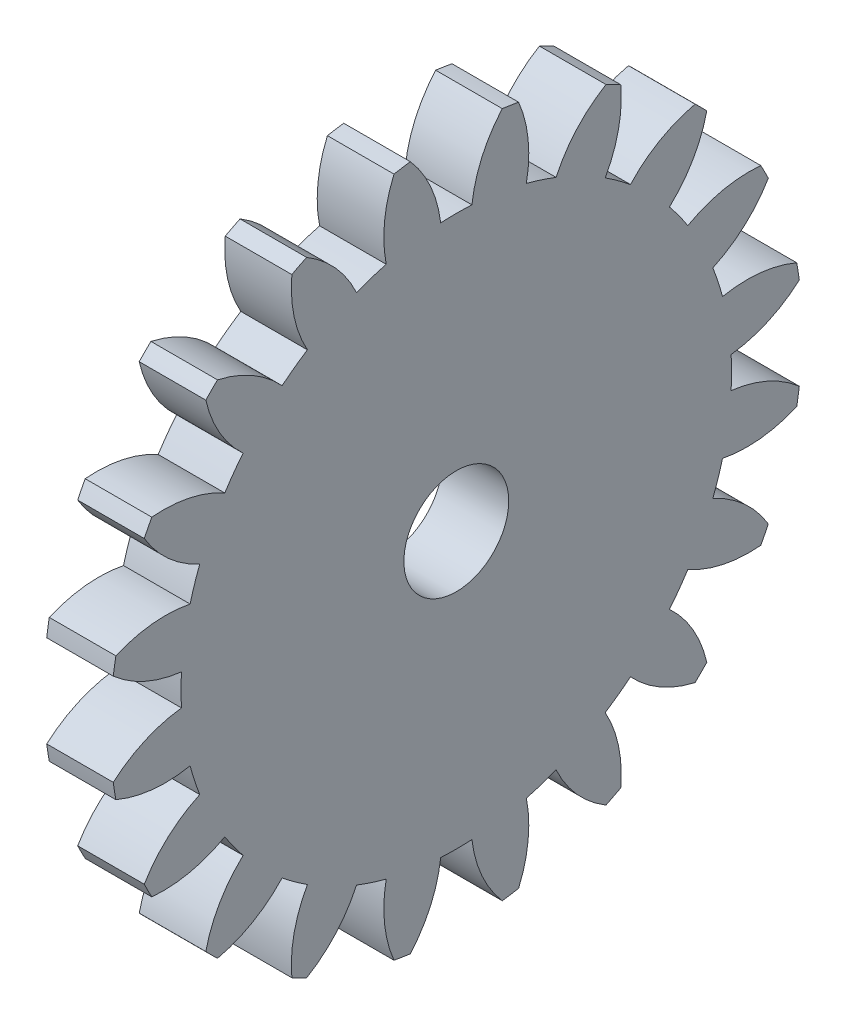
SolidWorks part; units mm, degrees
material "6061 Alloy"
ref_plane "Plane1" through (0, 0, 0) normal (0, 0, 1) x (1, 0, 0)
ref_plane "Plane2" through (0, 0, 0) normal (0, 1, 0) x (1, 0, 0)
ref_plane "Plane3" through (0, 0, 0) normal (1, 0, 0) x (0, 0, -1)
sketch "HoldingSke" plane through (0, 0, 0) normal (0, 1, 0) x (1, 0, 0)
  line L0 (0, 0) -> (0.3132, -0.114)
  line L1 (-15, 0) -> (100, 0) construction
  line L2 (0, 0) -> (-2.1039, 2.3779)
  line L3 (0, 0) -> (-11.863, 4.5341)
  line L4 (0, 0) -> (8.1152, 2.9537)
  line L5 (0, 0) -> (-46.8476, -17.4728)
  line L6 (0, 0) -> (-10.5278, -7.1032)
  line L7 (-2.1039, 2.3779) -> (8.6586, 51.2059)
  line L8 (-76.2, 54.61) -> (-74.4, 54.61)
  line L9 (-71.009, 38.7566) -> (-53.1078, 45.2721)
  line L10 (-76.2, 71.12) -> (104.1128, 71.12)
  line L11 (0, 0) -> (-12.7, 0)
  line L12 (-76.2, 101.6) -> (-76.093, 101.6)
  line L13 (24.9733, 27.94) -> (52.9518, 28.4284)
  line L14 (24.9733, 27.94) -> (24.9743, 27.94)
  line L15 (24.9733, 27.94) -> (100.4006, 29.5858)
  line L16 (-63.627, -3) -> (-12.827, -3)
  circle A0 centre (0, 0) radius 5
  circle A1 centre (0, 0) radius 26.249
  circle A2 centre (0, 0) radius 37.5
  circle A3 centre (0, 0) radius 5
  dimension "MHD" = 52.498
  dimension "Hub_dia" = 75
  dimension "Bore" = 10
  dimension "MBD" = 10
  dimension "Num_teeth" = 20
  dimension "Pitch" = 0.3333
  dimension "Overall_len" = 50
  dimension "Show_teeth" = 20
  dimension "Thickness" = 12.7
  dimension "OAL" = 50.0001
  dimension "T_dim" = 1.8
  dimension "Ap" = 20
  dimension "H" = 19.05
  dimension "Pitch_radius" = 180.3128
  dimension "Width" = 12.7
  dimension "Backlash" = 0.107
  dimension "Addendum_fac" = 1
  dimension "Dedendum_fac" = 1.25
  dimension "Clearance_fac" = 0.25
  dimension "Dedendum_add" = 0.001
  dimension "Module" = 3
sketch "BasProSke" plane through (0, 0, 0) normal (0, 1, 0) x (1, 0, 0)
  line L0 (-10, 0) -> (60, 0) construction
  line L1 (0, 0) -> (0, 33)
  line L2 (0, 0) -> (12.7, 0)
  line L3 (12.7, 0) -> (12.7, 33)
  line L4 (12.7, 33) -> (0, 33)
  dimension "Thickness" = 12.7
  dimension "Diameter" = 66
revolve "Base-Revolve" add sketch "BasProSke" angle 360 about L0
sketch "TooCutSke" plane through (0, 0, 0) normal (1, 0, 0) x (0, 0, -1)
  line L1 (0, 0) -> (0, 107) construction
  line L2 (0, 0) -> (-2.5409, 29.8922) construction
  line L3 (0, 0) -> (-9.3616, 59.1066) construction
  line L4 (-2.5409, 29.8922) -> (-4.6808, 29.5533) construction
  arc A0 (1.4893, 26.2067) -> (-1.4893, 26.2067) centre (0, 0) ccw
  arc A1 (4.4016, 32.7308) -> (-4.4016, 32.7308) centre (0, 0) ccw
  circle A2 centre (0, 0) radius 30 construction
  circle A3 centre (0, 0) radius 28.1908 construction
  arc A4 (-1.4893, 26.2067) -> (-4.4016, 32.7308) centre (-13.4064, 24.799) ccw
  arc A5 (4.4016, 32.7308) -> (1.4893, 26.2067) centre (13.4064, 24.799) ccw
  dimension "Root_dia" = 52.498
  dimension "Overcut_dia" = 66.0508
  dimension "Pitch_dia" = 60
  dimension "Base_dia" = 56.3816
  dimension "Flank_rad" = 12
  dimension "Half_ang" = 9
  dimension "Half_CT" = 2.1665
extrude "ToothCut" cut sketch "TooCutSke" along normal through all
fillet "Breaks" [suppressed] radius 0.06
fillet "RootFillets" [suppressed] radius 0.751
pattern_circular "TeethCuts" count 20 every 18 about axis through (-10, 0, 0) along (1, 0, 0) of "ToothCut", "RootFillets", "Breaks"
sketch "HubNeaOneSke" plane through (0, 0, 0) normal (-1, 0, 0) x (0, 0, 1)
  circle A0 centre (0, 0) radius 26.249
  dimension "Diameter" = 52.498
extrude "HubNearOne" [suppressed] add sketch "HubNeaOneSke" along normal blind 37.3001
sketch "HubNeaBotSke" plane through (0, 0, 0) normal (-1, 0, 0) x (0, 0, 1)
  circle A0 centre (0, 0) radius 26.249
  dimension "Diameter" = 52.498
extrude "HubNearBoth" [suppressed] add sketch "HubNeaBotSke" along normal blind 18.65
ref_plane "FarPln" through (12.7, 0, 0) normal (1, 0, 0) x (0, 0, -1)
sketch "HubFarSke" plane through (12.7, 0, 0) normal (1, 0, 0) x (0, 0, -1)
  circle A0 centre (0, 0) radius 26.249
  dimension "Diameter" = 52.498
extrude "HubFar" [suppressed] add sketch "HubFarSke" along normal blind 18.65
sketch "BorSke" plane through (0, 0, 0) normal (1, 0, 0) x (0, 0, -1)
  circle A0 centre (0, 0) radius 5
  dimension "Diameter" = 10
extrude "Bore" cut sketch "BorSke" along normal mid plane 100.0001
sketch "KeySke" plane through (0, 0, 0) normal (1, 0, 0) x (0, 0, -1)
  line L0 (-2, 0) -> (-2, 6.8)
  line L1 (-2, 6.8) -> (2, 6.8)
  line L2 (2, 6.8) -> (2, 0)
  line L3 (0, 0) -> (0, 34) construction
  line L4 (-2, 0) -> (2, 0)
  dimension "Offset" = 6.8
  dimension "Width" = 4
extrude "Keyway" [suppressed] cut sketch "KeySke" along normal mid plane 100.0001
pattern_circular "Keyway2" [suppressed] count 2 every 90 about axis through (-10, 0, 0) along (1, 0, 0)
sketch "Sketch1" plane through (12.7, 0, 0) normal (1, 0, 0) x (0, 0, -1)
  arc A80 (-32.7078, 4.3815) -> (-26.2067, 1.4893) centre (-24.799, 13.4064) ccw
  arc A81 (-26.2067, 1.4893) -> (-26.2067, -1.4893) centre (0, 0) ccw
  arc A82 (-26.2067, -1.4893) -> (-32.7078, -4.3815) centre (-24.799, -13.4064) ccw
  arc A83 (-32.7078, -4.3815) -> (-32.461, -5.9402) centre (0, 0) ccw
  arc A84 (-32.461, -5.9402) -> (-25.3843, -6.6819) centre (-27.728, 5.087) ccw
  arc A85 (-25.3843, -6.6819) -> (-24.4639, -9.5147) centre (0, 0) ccw
  arc A86 (-24.4639, -9.5147) -> (-29.7531, -14.2743) centre (-19.4424, -20.4136) ccw
  arc A87 (-29.7531, -14.2743) -> (-29.0366, -15.6805) centre (0, 0) ccw
  arc A88 (-29.0366, -15.6805) -> (-22.0771, -14.1991) centre (-27.9429, -3.7304) ccw
  arc A89 (-22.0771, -14.1991) -> (-20.3263, -16.6088) centre (0, 0) ccw
  arc A90 (-20.3263, -16.6088) -> (-23.8858, -22.7699) centre (-12.1827, -25.4225) ccw
  arc A91 (-23.8858, -22.7699) -> (-22.7699, -23.8858) centre (0, 0) ccw
  arc A92 (-22.7699, -23.8858) -> (-16.6088, -20.3263) centre (-25.4225, -12.1827) ccw
  arc A93 (-16.6088, -20.3263) -> (-14.1991, -22.0771) centre (0, 0) ccw
  arc A94 (-14.1991, -22.0771) -> (-15.6805, -29.0366) centre (-3.7304, -27.9429) ccw
  arc A95 (-15.6805, -29.0366) -> (-14.2743, -29.7531) centre (0, 0) ccw
  arc A96 (-14.2743, -29.7531) -> (-9.5147, -24.4639) centre (-20.4136, -19.4424) ccw
  arc A97 (-9.5147, -24.4639) -> (-6.6819, -25.3843) centre (0, 0) ccw
  arc A98 (-6.6819, -25.3843) -> (-5.9402, -32.461) centre (5.087, -27.728) ccw
  arc A99 (-5.9402, -32.461) -> (-4.3815, -32.7078) centre (0, 0) ccw
  arc A100 (-4.3815, -32.7078) -> (-1.4893, -26.2067) centre (-13.4064, -24.799) ccw
  arc A101 (-1.4893, -26.2067) -> (1.4893, -26.2067) centre (0, 0) ccw
  arc A102 (1.4893, -26.2067) -> (4.3815, -32.7078) centre (13.4064, -24.799) ccw
  arc A103 (4.3815, -32.7078) -> (5.9402, -32.461) centre (0, 0) ccw
  arc A104 (5.9402, -32.461) -> (6.6819, -25.3843) centre (-5.087, -27.728) ccw
  arc A105 (6.6819, -25.3843) -> (9.5147, -24.4639) centre (0, 0) ccw
  arc A106 (9.5147, -24.4639) -> (14.2743, -29.7531) centre (20.4136, -19.4424) ccw
  arc A107 (14.2743, -29.7531) -> (15.6805, -29.0366) centre (0, 0) ccw
  arc A108 (15.6805, -29.0366) -> (14.1991, -22.0771) centre (3.7304, -27.9429) ccw
  arc A109 (14.1991, -22.0771) -> (16.6088, -20.3263) centre (0, 0) ccw
  arc A110 (16.6088, -20.3263) -> (22.7699, -23.8858) centre (25.4225, -12.1827) ccw
  arc A111 (22.7699, -23.8858) -> (23.8858, -22.7699) centre (0, 0) ccw
  arc A112 (23.8858, -22.7699) -> (20.3263, -16.6088) centre (12.1827, -25.4225) ccw
  arc A113 (20.3263, -16.6088) -> (22.0771, -14.1991) centre (0, 0) ccw
  arc A114 (22.0771, -14.1991) -> (29.0366, -15.6805) centre (27.9429, -3.7304) ccw
  arc A115 (29.0366, -15.6805) -> (29.7531, -14.2743) centre (0, 0) ccw
  arc A116 (29.7531, -14.2743) -> (24.4639, -9.5147) centre (19.4424, -20.4136) ccw
  arc A117 (24.4639, -9.5147) -> (25.3843, -6.6819) centre (0, 0) ccw
  arc A118 (25.3843, -6.6819) -> (32.461, -5.9402) centre (27.728, 5.087) ccw
  arc A119 (32.461, -5.9402) -> (32.7078, -4.3815) centre (0, 0) ccw
  arc A120 (32.7078, -4.3815) -> (26.2067, -1.4893) centre (24.799, -13.4064) ccw
  arc A121 (26.2067, -1.4893) -> (26.2067, 1.4893) centre (0, 0) ccw
  arc A122 (26.2067, 1.4893) -> (32.7078, 4.3815) centre (24.799, 13.4064) ccw
  arc A123 (32.7078, 4.3815) -> (32.461, 5.9402) centre (0, 0) ccw
  arc A124 (32.461, 5.9402) -> (25.3843, 6.6819) centre (27.728, -5.087) ccw
  arc A125 (25.3843, 6.6819) -> (24.4639, 9.5147) centre (0, 0) ccw
  arc A126 (24.4639, 9.5147) -> (29.7531, 14.2743) centre (19.4424, 20.4136) ccw
  arc A127 (29.7531, 14.2743) -> (29.0366, 15.6805) centre (0, 0) ccw
  arc A128 (29.0366, 15.6805) -> (22.0771, 14.1991) centre (27.9429, 3.7304) ccw
  arc A129 (22.0771, 14.1991) -> (20.3263, 16.6088) centre (0, 0) ccw
  arc A130 (20.3263, 16.6088) -> (23.8858, 22.7699) centre (12.1827, 25.4225) ccw
  arc A131 (23.8858, 22.7699) -> (22.7699, 23.8858) centre (0, 0) ccw
  arc A132 (22.7699, 23.8858) -> (16.6088, 20.3263) centre (25.4225, 12.1827) ccw
  arc A133 (16.6088, 20.3263) -> (14.1991, 22.0771) centre (0, 0) ccw
  arc A134 (14.1991, 22.0771) -> (15.6805, 29.0366) centre (3.7304, 27.9429) ccw
  arc A135 (15.6805, 29.0366) -> (14.2743, 29.7531) centre (0, 0) ccw
  arc A136 (14.2743, 29.7531) -> (9.5147, 24.4639) centre (20.4136, 19.4424) ccw
  arc A137 (9.5147, 24.4639) -> (6.6819, 25.3843) centre (0, 0) ccw
  arc A138 (6.6819, 25.3843) -> (5.9402, 32.461) centre (-5.087, 27.728) ccw
  arc A139 (5.9402, 32.461) -> (4.3815, 32.7078) centre (0, 0) ccw
  arc A140 (4.3815, 32.7078) -> (1.4893, 26.2067) centre (13.4064, 24.799) ccw
  arc A141 (1.4893, 26.2067) -> (-1.4893, 26.2067) centre (0, 0) ccw
  arc A142 (-1.4893, 26.2067) -> (-4.3815, 32.7078) centre (-13.4064, 24.799) ccw
  arc A143 (-4.3815, 32.7078) -> (-5.9402, 32.461) centre (0, 0) ccw
  arc A144 (-5.9402, 32.461) -> (-6.6819, 25.3843) centre (5.087, 27.728) ccw
  arc A145 (-6.6819, 25.3843) -> (-9.5147, 24.4639) centre (0, 0) ccw
  arc A146 (-9.5147, 24.4639) -> (-14.2743, 29.7531) centre (-20.4136, 19.4424) ccw
  arc A147 (-14.2743, 29.7531) -> (-15.6805, 29.0366) centre (0, 0) ccw
  arc A148 (-15.6805, 29.0366) -> (-14.1991, 22.0771) centre (-3.7304, 27.9429) ccw
  arc A149 (-14.1991, 22.0771) -> (-16.6088, 20.3263) centre (0, 0) ccw
  arc A150 (-16.6088, 20.3263) -> (-22.7699, 23.8858) centre (-25.4225, 12.1827) ccw
  arc A151 (-22.7699, 23.8858) -> (-23.8858, 22.7699) centre (0, 0) ccw
  arc A152 (-23.8858, 22.7699) -> (-20.3263, 16.6088) centre (-12.1827, 25.4225) ccw
  arc A153 (-20.3263, 16.6088) -> (-22.0771, 14.1991) centre (0, 0) ccw
  arc A154 (-22.0771, 14.1991) -> (-29.0366, 15.6805) centre (-27.9429, 3.7304) ccw
  arc A155 (-29.0366, 15.6805) -> (-29.7531, 14.2743) centre (0, 0) ccw
  arc A156 (-29.7531, 14.2743) -> (-24.4639, 9.5147) centre (-19.4424, 20.4136) ccw
  arc A157 (-24.4639, 9.5147) -> (-25.3843, 6.6819) centre (0, 0) ccw
  arc A158 (-25.3843, 6.6819) -> (-32.461, 5.9402) centre (-27.728, -5.087) ccw
  arc A159 (-32.461, 5.9402) -> (-32.7078, 4.3815) centre (0, 0) ccw
  arc A160 (-32.7078, 4.3815) -> (-26.2067, 1.4893) centre (-24.799, 13.4064) ccw
  arc A161 (-26.2067, 1.4893) -> (-26.2067, -1.4893) centre (0, 0) ccw
  arc A162 (-26.2067, -1.4893) -> (-32.7078, -4.3815) centre (-24.799, -13.4064) ccw
  arc A163 (-32.7078, -4.3815) -> (-32.461, -5.9402) centre (0, 0) ccw
  arc A164 (-32.461, -5.9402) -> (-25.3843, -6.6819) centre (-27.728, 5.087) ccw
  arc A165 (-25.3843, -6.6819) -> (-24.4639, -9.5147) centre (0, 0) ccw
  arc A166 (-24.4639, -9.5147) -> (-29.7531, -14.2743) centre (-19.4424, -20.4136) ccw
  arc A167 (-29.7531, -14.2743) -> (-29.0366, -15.6805) centre (0, 0) ccw
  arc A168 (-29.0366, -15.6805) -> (-22.0771, -14.1991) centre (-27.9429, -3.7304) ccw
  arc A169 (-22.0771, -14.1991) -> (-20.3263, -16.6088) centre (0, 0) ccw
  arc A170 (-20.3263, -16.6088) -> (-23.8858, -22.7699) centre (-12.1827, -25.4225) ccw
  arc A171 (-23.8858, -22.7699) -> (-22.7699, -23.8858) centre (0, 0) ccw
  arc A172 (-22.7699, -23.8858) -> (-16.6088, -20.3263) centre (-25.4225, -12.1827) ccw
  arc A173 (-16.6088, -20.3263) -> (-14.1991, -22.0771) centre (0, 0) ccw
  arc A174 (-14.1991, -22.0771) -> (-15.6805, -29.0366) centre (-3.7304, -27.9429) ccw
  arc A175 (-15.6805, -29.0366) -> (-14.2743, -29.7531) centre (0, 0) ccw
  arc A176 (-14.2743, -29.7531) -> (-9.5147, -24.4639) centre (-20.4136, -19.4424) ccw
  arc A177 (-9.5147, -24.4639) -> (-6.6819, -25.3843) centre (0, 0) ccw
  arc A178 (-6.6819, -25.3843) -> (-5.9402, -32.461) centre (5.087, -27.728) ccw
  arc A179 (-5.9402, -32.461) -> (-4.3815, -32.7078) centre (0, 0) ccw
  arc A180 (-4.3815, -32.7078) -> (-1.4893, -26.2067) centre (-13.4064, -24.799) ccw
  arc A181 (-1.4893, -26.2067) -> (1.4893, -26.2067) centre (0, 0) ccw
  arc A182 (1.4893, -26.2067) -> (4.3815, -32.7078) centre (13.4064, -24.799) ccw
  arc A183 (4.3815, -32.7078) -> (5.9402, -32.461) centre (0, 0) ccw
  arc A184 (5.9402, -32.461) -> (6.6819, -25.3843) centre (-5.087, -27.728) ccw
  arc A185 (6.6819, -25.3843) -> (9.5147, -24.4639) centre (0, 0) ccw
  arc A186 (9.5147, -24.4639) -> (14.2743, -29.7531) centre (20.4136, -19.4424) ccw
  arc A187 (14.2743, -29.7531) -> (15.6805, -29.0366) centre (0, 0) ccw
  arc A188 (15.6805, -29.0366) -> (14.1991, -22.0771) centre (3.7304, -27.9429) ccw
  arc A189 (14.1991, -22.0771) -> (16.6088, -20.3263) centre (0, 0) ccw
  arc A190 (16.6088, -20.3263) -> (22.7699, -23.8858) centre (25.4225, -12.1827) ccw
  arc A191 (22.7699, -23.8858) -> (23.8858, -22.7699) centre (0, 0) ccw
  arc A192 (23.8858, -22.7699) -> (20.3263, -16.6088) centre (12.1827, -25.4225) ccw
  arc A193 (20.3263, -16.6088) -> (22.0771, -14.1991) centre (0, 0) ccw
  arc A194 (22.0771, -14.1991) -> (29.0366, -15.6805) centre (27.9429, -3.7304) ccw
  arc A195 (29.0366, -15.6805) -> (29.7531, -14.2743) centre (0, 0) ccw
  arc A196 (29.7531, -14.2743) -> (24.4639, -9.5147) centre (19.4424, -20.4136) ccw
  arc A197 (24.4639, -9.5147) -> (25.3843, -6.6819) centre (0, 0) ccw
  arc A198 (25.3843, -6.6819) -> (32.461, -5.9402) centre (27.728, 5.087) ccw
  arc A199 (32.461, -5.9402) -> (32.7078, -4.3815) centre (0, 0) ccw
  arc A200 (32.7078, -4.3815) -> (26.2067, -1.4893) centre (24.799, -13.4064) ccw
  arc A201 (26.2067, -1.4893) -> (26.2067, 1.4893) centre (0, 0) ccw
  arc A202 (26.2067, 1.4893) -> (32.7078, 4.3815) centre (24.799, 13.4064) ccw
  arc A203 (32.7078, 4.3815) -> (32.461, 5.9402) centre (0, 0) ccw
  arc A204 (32.461, 5.9402) -> (25.3843, 6.6819) centre (27.728, -5.087) ccw
  arc A205 (25.3843, 6.6819) -> (24.4639, 9.5147) centre (0, 0) ccw
  arc A206 (24.4639, 9.5147) -> (29.7531, 14.2743) centre (19.4424, 20.4136) ccw
  arc A207 (29.7531, 14.2743) -> (29.0366, 15.6805) centre (0, 0) ccw
  arc A208 (29.0366, 15.6805) -> (22.0771, 14.1991) centre (27.9429, 3.7304) ccw
  arc A209 (22.0771, 14.1991) -> (20.3263, 16.6088) centre (0, 0) ccw
  arc A210 (20.3263, 16.6088) -> (23.8858, 22.7699) centre (12.1827, 25.4225) ccw
  arc A211 (23.8858, 22.7699) -> (22.7699, 23.8858) centre (0, 0) ccw
  arc A212 (22.7699, 23.8858) -> (16.6088, 20.3263) centre (25.4225, 12.1827) ccw
  arc A213 (16.6088, 20.3263) -> (14.1991, 22.0771) centre (0, 0) ccw
  arc A214 (14.1991, 22.0771) -> (15.6805, 29.0366) centre (3.7304, 27.9429) ccw
  arc A215 (15.6805, 29.0366) -> (14.2743, 29.7531) centre (0, 0) ccw
  arc A216 (14.2743, 29.7531) -> (9.5147, 24.4639) centre (20.4136, 19.4424) ccw
  arc A217 (9.5147, 24.4639) -> (6.6819, 25.3843) centre (0, 0) ccw
  arc A218 (6.6819, 25.3843) -> (5.9402, 32.461) centre (-5.087, 27.728) ccw
  arc A219 (5.9402, 32.461) -> (4.3815, 32.7078) centre (0, 0) ccw
  arc A220 (4.3815, 32.7078) -> (1.4893, 26.2067) centre (13.4064, 24.799) ccw
  arc A221 (1.4893, 26.2067) -> (-1.4893, 26.2067) centre (0, 0) ccw
  arc A222 (-1.4893, 26.2067) -> (-4.3815, 32.7078) centre (-13.4064, 24.799) ccw
  arc A223 (-4.3815, 32.7078) -> (-5.9402, 32.461) centre (0, 0) ccw
  arc A224 (-5.9402, 32.461) -> (-6.6819, 25.3843) centre (5.087, 27.728) ccw
  arc A225 (-6.6819, 25.3843) -> (-9.5147, 24.4639) centre (0, 0) ccw
  arc A226 (-9.5147, 24.4639) -> (-14.2743, 29.7531) centre (-20.4136, 19.4424) ccw
  arc A227 (-14.2743, 29.7531) -> (-15.6805, 29.0366) centre (0, 0) ccw
  arc A228 (-15.6805, 29.0366) -> (-14.1991, 22.0771) centre (-3.7304, 27.9429) ccw
  arc A229 (-14.1991, 22.0771) -> (-16.6088, 20.3263) centre (0, 0) ccw
  arc A230 (-16.6088, 20.3263) -> (-22.7699, 23.8858) centre (-25.4225, 12.1827) ccw
  arc A231 (-22.7699, 23.8858) -> (-23.8858, 22.7699) centre (0, 0) ccw
  arc A232 (-23.8858, 22.7699) -> (-20.3263, 16.6088) centre (-12.1827, 25.4225) ccw
  arc A233 (-20.3263, 16.6088) -> (-22.0771, 14.1991) centre (0, 0) ccw
  arc A234 (-22.0771, 14.1991) -> (-29.0366, 15.6805) centre (-27.9429, 3.7304) ccw
  arc A235 (-29.0366, 15.6805) -> (-29.7531, 14.2743) centre (0, 0) ccw
  arc A236 (-29.7531, 14.2743) -> (-24.4639, 9.5147) centre (-19.4424, 20.4136) ccw
  arc A237 (-24.4639, 9.5147) -> (-25.3843, 6.6819) centre (0, 0) ccw
  arc A238 (-25.3843, 6.6819) -> (-32.461, 5.9402) centre (-27.728, -5.087) ccw
  arc A239 (-32.461, 5.9402) -> (-32.7078, 4.3815) centre (0, 0) ccw
  dimension "D1" = 0
extrude "Cut-Extrude1" cut sketch "Sketch1" against normal blind 6.35
equation "' \"Module@HoldingSke\" = 6.35"
equation "' \"Num_teeth@HoldingSke\" = 12"
equation "' \"Ap@HoldingSke\" =  20"
equation "' \"Ap@HoldingSke\" = 20"
equation "' \"Width@HoldingSke\" = 0.5 * 25.4"
equation "' \"Hub_dia@HoldingSke\"= 1 * 25.4"
equation "' \"Hub_dia@HoldingSke\" = 1 * 25.4"
equation "' \"Overall_len@HoldingSke\" = 1.0 * 25.4"
equation "' \"Bore@HoldingSke\" = 0.75 * 25.4"
equation "' \"T_dim@HoldingSke\" = 0.1 * 25.4"
equation "' \"Width@KeySke\" = 0.25 * 25.4"
equation "' \"Show_teeth@HoldingSke\" = 13"
equation "' \"Backlash@HoldingSke\" = 0.009 * 25.4"
equation "' \"Addendum_fac@HoldingSke\" = 1.0"
equation "' \"Dedendum_fac@HoldingSke\" = 1.25"
equation "' \"Dedendum_add@HoldingSke\" = 0.00005 * 25.4"
equation "' \"Clearance_fac@HoldingSke\" = 0.25"
equation "\"Pitch@HoldingSke\" = 1 / \"Module@HoldingSke\""
equation "\"Overcut_dia@TooCutSke\" = (\"Num_teeth@HoldingSke\" + 2 * \"Addendum_fac@HoldingSke\") / \"Pitch@HoldingSke\" + 0.002 * 25.4"
equation "\"Pitch_dia@TooCutSke\" = \"Num_teeth@HoldingSke\" / \"Pitch@HoldingSke\""
equation "\"Base_dia@TooCutSke\" = \"Num_teeth@HoldingSke\" / \"Pitch@HoldingSke\" * cos((\"Ap@HoldingSke\"  * 3.14159265 / 180))"
equation "\"Root_dia@TooCutSke\" = (\"Num_teeth@HoldingSke\" + 2) / \"Pitch@HoldingSke\" - 2 * (\"Addendum_fac@HoldingSke\" + \"Dedendum_fac@HoldingSke\") / \"Pitch@HoldingSke\" - \"Dedendum_add@HoldingSke\" * 2"
equation "\"Half_ang@TooCutSke\" = 180 / \"Num_teeth@HoldingSke\""
equation "\"Half_CT@TooCutSke\" = \"Num_teeth@HoldingSke\" / \"Pitch@HoldingSke\" * sin((3.14159265 / 2 / \"Num_teeth@HoldingSke\")) / 2 - 7 * \"Backlash@HoldingSke\" / 4"
equation "\"Flank_rad@TooCutSke\" = \"Num_teeth@HoldingSke\" / \"Pitch@HoldingSke\" / 5"
equation "\"Radius@RootFillets\" = \"Clearance_fac@HoldingSke\" / \"Pitch@HoldingSke\" + \"Dedendum_add@HoldingSke\""
equation "\"Break_rad@Breaks\" = 0.02 / \"Pitch@HoldingSke\""
equation "\"Thickness@HoldingSke\" = \"Width@HoldingSke\""
equation "\"OAL@HoldingSke\" = \"Thickness@HoldingSke\""
equation "\"MHD@HoldingSke\" = (\"Num_teeth@HoldingSke\" + 2) / \"Pitch@HoldingSke\" - 2 * (\"Addendum_fac@HoldingSke\" + \"Dedendum_fac@HoldingSke\")  / \"Pitch@HoldingSke\" - \"Dedendum_add@HoldingSke\" * 2"
equation "\"MBD@HoldingSke\" = (\"Num_teeth@HoldingSke\" + 2) / \"Pitch@HoldingSke\" - 2 * (\"Addendum_fac@HoldingSke\" + \"Dedendum_fac@HoldingSke\")  / \"Pitch@HoldingSke\" - \"Dedendum_add@HoldingSke\" * 2 - 0.002 * 25.4"
equation "\"MHD@HoldingSke\" = ((sgn( \"MHD@HoldingSke\" - \"Hub_dia@HoldingSke\" )-1)*( \"MHD@HoldingSke\" - \"Hub_dia@HoldingSke\" ))/-2+ \"Hub_dia@HoldingSke\""
equation "\"MBD@HoldingSke\" = ((sgn( \"MBD@HoldingSke\" - \"Bore@HoldingSke\" )-1)*( \"MBD@HoldingSke\" - \"Bore@HoldingSke\" ))/-2+ \"Bore@HoldingSke\""
equation "\"OAL@HoldingSke\" = ((sgn( \"OAL@HoldingSke\" - \"Overall_len@HoldingSke\" )+1)*( \"OAL@HoldingSke\" - \"Overall_len@HoldingSke\" ))/2 + \"Overall_len@HoldingSke\" + 0.000002 * 25.4"
equation "\"Num_teeth@TeethCuts\" = int( \"Show_teeth@HoldingSke\" ) + 1"
equation "\"Num_teeth@TeethCuts\" = ((sgn( \"Num_teeth@TeethCuts\" - \"Num_teeth@HoldingSke\" )-1)*( \"Num_teeth@TeethCuts\" - \"Num_teeth@HoldingSke\" ))/-2+ \"Num_teeth@HoldingSke\""
equation "\"Num_teeth@TeethCuts\" = ((sgn( \"Num_teeth@TeethCuts\" - 2.0)+1)*( \"Num_teeth@TeethCuts\" - 2.0))/2 +2.0"
equation "\"Angle@TeethCuts\" = 360.0 / \"Num_teeth@HoldingSke\""
equation "\"Diameter@BasProSke\" = (\"Num_teeth@HoldingSke\" + 2 * \"Addendum_fac@HoldingSke\") / \"Pitch@HoldingSke\""
equation "\"Thickness@BasProSke\"  = \"Thickness@HoldingSke\""
equation "' \"Fillet_rad@BasProSke\" =  \"Thickness@HoldingSke\" * 0.05"
equation "' \"Fillet_rad@BasProSke\" = \"Thickness@HoldingSke\" * 0.05"
equation "\"MHD@HoldingSke\" = ((sgn( \"MHD@HoldingSke\" - \"Root_dia@TooCutSke\" )-1)*( \"MHD@HoldingSke\" - \"Root_dia@TooCutSke\" ))/-2+ \"Root_dia@TooCutSke\""
equation "\"Diameter@HubNeaOneSke\" = \"MHD@HoldingSke\""
equation "\"Length@HubNearOne\" = \"OAL@HoldingSke\" - \"Thickness@BasProSke\""
equation "\"Diameter@HubNeaBotSke\" = \"MHD@HoldingSke\""
equation "\"Length@HubNearBoth\" = ( \"OAL@HoldingSke\" - \"Thickness@BasProSke\" ) / 2.0"
equation "\"Thickness@FarPln\" = \"Thickness@BasProSke\""
equation "\"Diameter@HubFarSke\" = \"MHD@HoldingSke\""
equation "\"Length@HubFar\" = ( \"OAL@HoldingSke\" - \"Thickness@BasProSke\" ) / 2.0"
equation "\"Diameter@BorSke\" = \"MBD@HoldingSke\""
equation "\"D1@Bore\" = \"OAL@HoldingSke\" * 2.0"
equation "\"D1@Keyway\" = \"OAL@HoldingSke\" * 2.0"
equation "\"Offset@KeySke\" = \"T_dim@HoldingSke\" + \"MBD@HoldingSke\" / 2.0"
